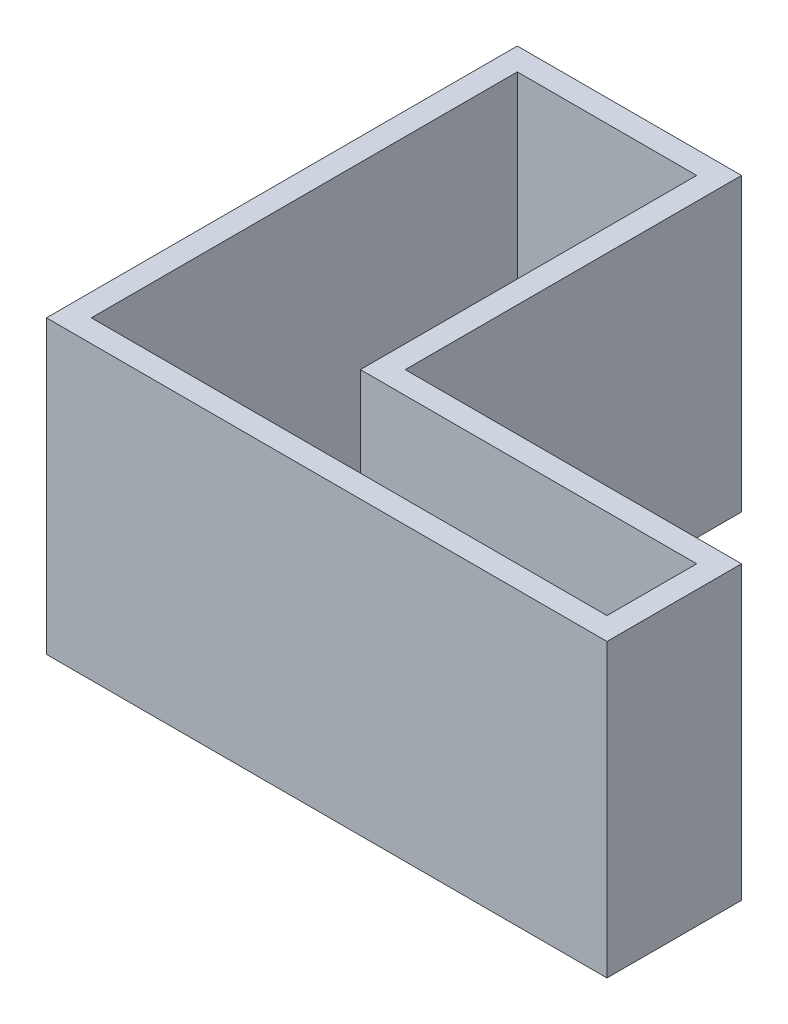
SolidWorks part; units mm, degrees
ref_plane "前视基准面" through (0, 0, 0) normal (0, 0, 1) x (1, 0, 0)
ref_plane "上视基准面" through (0, 0, 0) normal (0, 1, 0) x (1, 0, 0)
ref_plane "右视基准面" through (0, 0, 0) normal (1, 0, 0) x (0, 0, -1)
sketch "草图1" plane through (0, 0, 0) normal (0, 1, 0) x (1, 0, 0)
  line L0 (0, 0) -> (0, 21)
  line L1 (0, 21) -> (10, 21)
  line L2 (10, 21) -> (10, 6)
  line L3 (10, 6) -> (25, 6)
  line L4 (25, 6) -> (25, 0)
  line L5 (25, 0) -> (0, 0)
  line L6 (1, 20) -> (9, 20)
  line L7 (9, 20) -> (9, 5)
  line L8 (9, 5) -> (24, 5)
  line L9 (24, 5) -> (24, 1)
  line L10 (24, 1) -> (1, 1)
  line L11 (1, 1) -> (1, 20)
  dimension "D1" = 15
  dimension "D2" = 15
  dimension "D3" = 10
  dimension "D4" = 6
  dimension "D5" = 1
extrude "凸台-拉伸1" add sketch "草图1" along normal blind 12
sketch "草图3" plane through (0, 0, 0) normal (0, -1, 0) x (1, 0, 0)
  line L0 (10, -21) -> (0, -21) construction
  line L1 (10, -6) -> (10, -21) construction
  line L2 (25, -6) -> (10, -6) construction
  line L3 (25, 0) -> (25, -6) construction
  line L4 (0, 0) -> (25, 0) construction
  line L5 (0, -21) -> (0, 0) construction
  line L6 (10, -21) -> (0, -21)
  line L7 (10, -6) -> (10, -21)
  line L8 (25, -6) -> (10, -6)
  line L9 (25, 0) -> (25, -6)
  line L10 (0, 0) -> (25, 0)
  line L11 (0, -21) -> (0, 0)
extrude "凸台-拉伸2" add sketch "草图3" along normal blind 1
